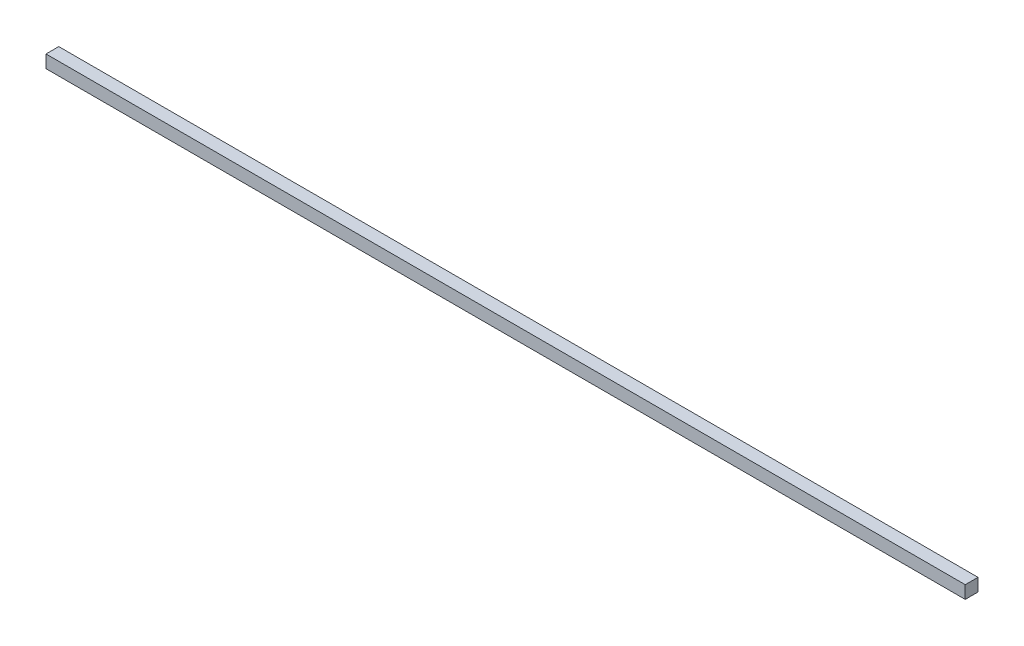
SolidWorks part; units mm, degrees
ref_plane "Front Plane" through (0, 0, 0) normal (0, 0, 1) x (1, 0, 0)
ref_plane "Top Plane" through (0, 0, 0) normal (0, 1, 0) x (1, 0, 0)
ref_plane "Right Plane" through (0, 0, 0) normal (1, 0, 0) x (0, 0, -1)
sketch "Sketch1" plane through (0, 0, 0) normal (0, 0, 1) x (1, 0, 0)
  line L1 (0, 6.35) -> (457.2, 6.35)
  line L2 (0, 6.35) -> (0, 0)
  line L3 (0, 0) -> (457.2, 0)
  line L4 (457.2, 6.35) -> (457.2, 0)
  point P4 (0, 0)
  point P6 (0, 0)
  dimension "D2" = 6.35
extrude "Boss-Extrude1" add sketch "Sketch1" along normal blind 6.35
